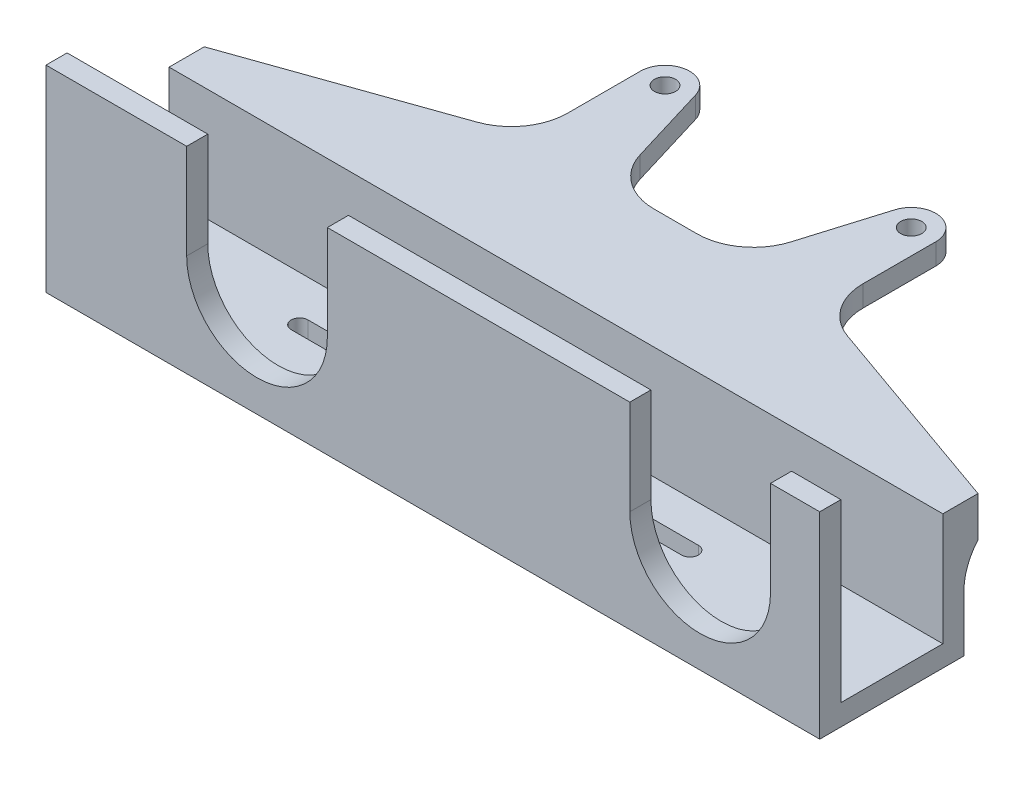
SolidWorks part; units mm, degrees
ref_plane "Front Plane" through (0, 0, 0) normal (0, 0, 1) x (1, 0, 0)
ref_plane "Top Plane" through (0, 0, 0) normal (0, 1, 0) x (1, 0, 0)
ref_plane "Right Plane" through (0, 0, 0) normal (1, 0, 0) x (0, 0, -1)
ref_plane "Plane1" through (0, -88.5, 0) normal (0, 1, 0) x (1, 0, 0)
sketch "Location" plane through (0, -88.5, 0) normal (0, 1, 0) x (1, 0, 0)
  line L0 (0, 0) -> (-17.5, 0)
  line L1 (-17.5, 0) -> (-17.5, -102.2)
  dimension "D1" = 102.2
  dimension "D2" = 17.5
sketch "Sketch2" plane through (0, -88.5, 0) normal (0, 1, 0) x (1, 0, 0)
  line L2 (-9, -118.2) -> (-14.1501, -101.186)
  line L3 (-9, -118.2) -> (0, -118.2)
  line L4 (0, -118.2) -> (0, -135.2)
  line L5 (0, -135.2) -> (-55, -135.2)
  line L7 (-21, -102.2) -> (-21, -118.2)
  line L8 (0, -56.21) -> (0, 56.21) construction
  line L10 (-55, -135.2) -> (-55, -130.2)
  line L11 (-55, -130.2) -> (-21, -118.2)
  circle A0 centre (-17.5, -102.2) radius 1.5
  arc A2 (-21, -102.2) -> (-14.1501, -101.186) centre (-17.5, -102.2) cw
  dimension "D1" = 3
  dimension "D2" = 2
  dimension "D3" = 33
  dimension "D4" = 55
  dimension "D5" = 5
  dimension "D6" = 17
  dimension "D7" = 9
extrude "Boss-Extrude1" add sketch "Sketch2" against normal blind 3
fillet "Fillet2" radius 8 2 edges at (-9, -90, 118.2) (-21, -90, 118.2)
mirror "Mirror1" about plane through (0, 0, 0) normal (1, 0, 0) of "Fillet2", "Boss-Extrude1"
sketch "Sketch4" plane through (0, 0, 0) normal (1, 0, 0) x (0, 0, -1)
  line L0 (-135.2, -91.5) -> (-135.2, -104.5)
  line L1 (-135.2, -104.5) -> (-149.7, -104.5)
  line L2 (-149.7, -104.5) -> (-149.7, -79.5)
  line L3 (-149.7, -79.5) -> (-152.7, -79.5)
  line L4 (-152.7, -79.5) -> (-152.7, -107.5)
  line L5 (-152.7, -107.5) -> (-132.2, -107.5)
  line L6 (-132.2, -107.5) -> (-132.2, -91.5)
  line L7 (-132.2, -91.5) -> (-135.2, -91.5)
  line L8 (-103.7, -91.5) -> (-100.7, -91.5) construction
  line L9 (-135.2, -91.5) -> (-135.2, -88.5) construction
  line L10 (60.5, -88.5) -> (-60.5, -88.5) construction
  dimension "D1" = 3
  dimension "D2" = 16
  dimension "D3" = 3
  dimension "D4" = 14.5
  dimension "D5" = 9
extrude "Boss-Extrude2" add sketch "Sketch4" along normal through all and the other way through all
sketch "Sketch5" plane through (0, 0, 152.7) normal (0, 0, 1) x (1, 0, 0)
  line L0 (-35, -93) -> (-35, -73)
  line L1 (-35, -73) -> (-15, -73)
  line L2 (-15, -73) -> (-15, -93)
  line L3 (28, -93) -> (28, -73)
  line L4 (28, -73) -> (48, -73)
  line L5 (48, -73) -> (48, -93)
  arc A0 (-35, -93) -> (-15, -93) centre (-25, -93) ccw
  arc A1 (28, -93) -> (48, -93) centre (38, -93) ccw
  dimension "D1" = 25
  dimension "D2" = 10
  dimension "D5" = 38
  dimension "D6" = 10
  dimension "D3" = 20
  dimension "D4" = 93
extrude "Cut-Extrude1" cut sketch "Sketch5" against normal up to next
ref_plane "Plane2" through (-17.5, 0, 0) normal (1, 0, 0) x (0, 0, -1)
sketch "Sketch6" plane through (-17.5, 0, 0) normal (1, 0, 0) x (0, 0, -1)
  line L0 (-112.2, -91.5) -> (-132.2, -107.5)
  line L1 (-103.7, -91.5) -> (-100.7, -91.5) construction
  line L2 (-132.2, -107.5) -> (-132.2, -91.5) construction
  line L3 (-152.7, -107.5) -> (-132.2, -107.5) construction
  dimension "D1" = 20
rib "Rib1" sketch "Sketch6" sketch "Sketch6" thickness 5 extrusion direction parallel to sketch draft on no parameters "D1"=5
mirror "Mirror2" about plane through (0, 0, 0) normal (1, 0, 0) of "Rib1"
fillet "Fillet3" radius 8 3 edges at (-37.5, -91.5, 132.2) (37.5, -91.5, 132.2) (0, -91.5, 132.2)
sketch "Sketch7" plane through (0, -104.5, 0) normal (0, 1, 0) x (1, 0, 0)
  line L0 (-30, -141.65) -> (25.5, -141.65) construction
  line L4 (0, -135.2) -> (0, -149.7) construction
  line L5 (-55, -135.2) -> (55, -135.2) construction
  line L6 (55, -149.7) -> (-55, -149.7) construction
  line L7 (-30, -140.45) -> (25.5, -140.45)
  line L8 (-30, -142.85) -> (25.5, -142.85)
  arc A2 (-30, -140.45) -> (-30, -142.85) centre (-30, -141.65) ccw
  arc A3 (25.5, -142.85) -> (25.5, -140.45) centre (25.5, -141.65) ccw
  point P2 (-2.25, -141.65)
  point P7 (2.0195, -144.3822)
  point P10 (0, -142.45)
  point P11 (0, -142.45)
  dimension "D2" = 1.2
  dimension "D1" = 0.8
  dimension "D3" = 30
  dimension "D4" = 25.5
extrude "Cut-Extrude2" cut sketch "Sketch7" against normal through all
